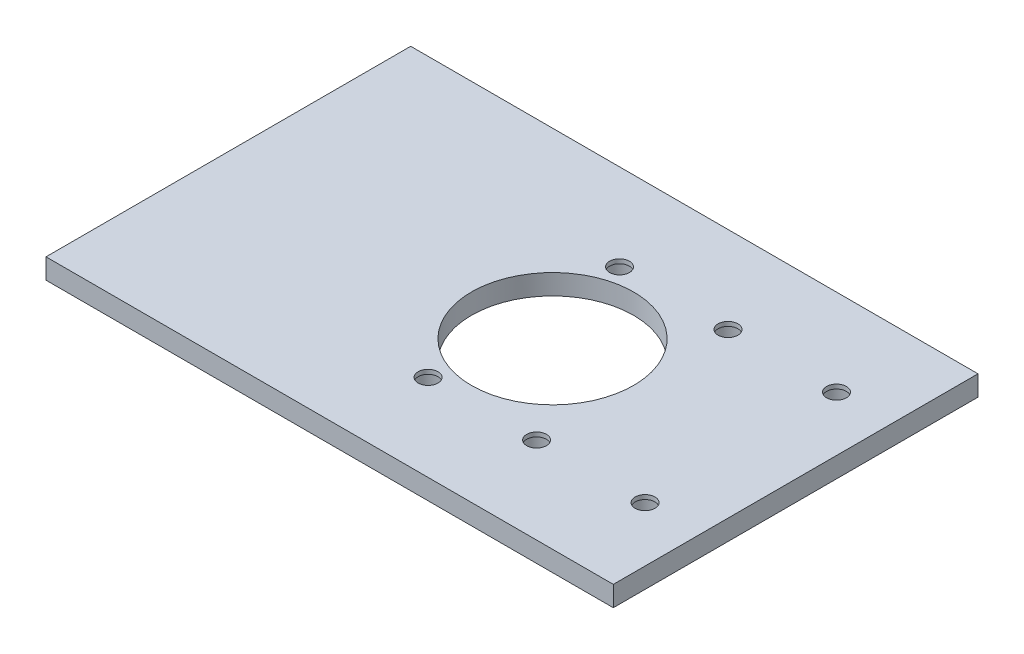
SolidWorks part; units mm, degrees
material "6061-T6 (SS)"
ref_plane "Front Plane" through (0, 0, 0) normal (0, 0, 1) x (1, 0, 0)
ref_plane "Top Plane" through (0, 0, 0) normal (0, 1, 0) x (1, 0, 0)
ref_plane "Right Plane" through (0, 0, 0) normal (1, 0, 0) x (0, 0, -1)
sketch "Sketch1" plane through (0, 0, 0) normal (0, 1, 0) x (1, 0, 0)
  line L1 (38.1, 28.575) -> (-50.8, 28.575)
  line L2 (38.1, 28.575) -> (38.1, -28.575)
  line L3 (38.1, -28.575) -> (-50.8, -28.575)
  line L4 (-50.8, 28.575) -> (-50.8, -28.575)
  point P0 (0, 0)
  dimension "D1" = 50.8
  dimension "D2" = 28.575
  dimension "D3" = 28.575
  dimension "D4" = 38.1
extrude "Boss-Extrude1" add sketch "Sketch1" along normal mid plane 3.175
sketch "Sketch2" plane through (0, 1.5875, 0) normal (0, 1, 0) x (1, 0, 0)
  line L0 (-31.75, 19.05) -> (-44.45, 19.05)
  line L8 (-31.75, 19.05) -> (-31.75, -19.05)
  line L9 (-31.75, -19.05) -> (-44.45, -19.05)
  line L10 (-44.45, 19.05) -> (-44.45, -19.05)
  line L11 (-31.75, 19.05) -> (-44.45, -19.05) construction
  line L12 (-31.75, -19.05) -> (-44.45, 19.05) construction
  circle A0 centre (0, 0) radius 12.7
  point P8 (-38.1, 0)
  dimension "D1" = 25.4
  dimension "D2" = 12.7
  dimension "D3" = 38.1
  dimension "D4" = 38.1
  dimension "D5" = 38.1
extrude "Cut-Extrude1" cut sketch "Sketch2" against normal up to surface (3.175 mm away) contours A0 up to face at (-6.35, -1.5875, 0)
sketch "Sketch6" plane through (0, 1.5875, 0) normal (0, 1, 0) x (1, 0, 0)
  line L0 (30, -12.2) -> (-9, -12.2)
  line L1 (-12, -12.7) -> (-12, -9.2)
  line L2 (-12, -12.7) -> (-6, -17.8)
  line L3 (-6, -17.8) -> (32.6, -17.8)
  line L4 (32.6, -17.8) -> (38.6, -12.7)
  line L5 (38.6, -12.7) -> (38.6, 12.7)
  line L6 (38.6, 12.7) -> (32.6, 17.8)
  line L7 (32.6, 17.8) -> (-6, 17.8)
  line L8 (-12, 12.7) -> (-6, 17.8)
  line L9 (-12, 9.2) -> (-12, 12.7)
  line L10 (-9, 12.2) -> (30, 12.2)
  line L11 (33, 9.2) -> (33, -9.2)
  line L12 (30, 11.2) -> (-9, 11.2)
  line L13 (-11, 9.2) -> (-11, -9.2)
  line L14 (-9, -11.2) -> (30, -11.2)
  line L15 (32, -9.2) -> (32, 9.2)
  circle A0 centre (29.5, 15) radius 1.35
  circle A1 centre (29.5, -15) radius 1.35
  circle A2 centre (35.8, 8.5) radius 1.35
  circle A3 centre (12.5, 15) radius 1.35
  circle A4 centre (-4.5, 15) radius 1.35
  circle A5 centre (35.8, -8.5) radius 1.35
  circle A6 centre (12.5, -15) radius 1.35
  circle A7 centre (-4.5, -15) radius 1.35
  arc A8 (-12, -9.2) -> (-9, -12.2) centre (-9, -9.2) ccw
  arc A9 (-9, 12.2) -> (-12, 9.2) centre (-9, 9.2) ccw
  arc A10 (33, 9.2) -> (30, 12.2) centre (30, 9.2) ccw
  arc A11 (30, -12.2) -> (33, -9.2) centre (30, -9.2) ccw
  circle A12 centre (0, 0) radius 2.85
  spline S0 degree 3 poles (32, 9.2) (31.9994, 10.252) (31.055, 11.1994) (30, 11.2) knots 0 0 0 0 1 1 1 1
  spline S1 degree 3 poles (-9, 11.2) (-10.052, 11.1994) (-10.9994, 10.255) (-11, 9.2) knots 0 0 0 0 1 1 1 1
  spline S2 degree 3 poles (-11, -9.2) (-10.9994, -10.252) (-10.055, -11.1994) (-9, -11.2) knots 0 0 0 0 1 1 1 1
  spline S3 degree 3 poles (30, -11.2) (31.052, -11.1994) (31.9994, -10.255) (32, -9.2) knots 0 0 0 0 1 1 1 1
hole_wizard "CBORE for M2.5 SHCS1" positions "Sketch9" profile "Sketch10" counterbore size "M2.5" standard "ANSI Metric"
sketch "Sketch9" plane through (0, -1.5875, 0) normal (0, -1, 0) x (-1, 0, 0)
  point P0 (-29.5, 15)
  point P3 (-12.5, 15)
  point P6 (4.5, 15)
  point P9 (-29.5, -15)
  point P12 (-12.5, -15)
  point P15 (4.5, -15)
sketch "Sketch10" plane through (29.5, -1.5875, -15) normal (1, 0, 0) x (0, 0, -1)
  line L0 (0, 0) -> (0, 153.3313)
  line L1 (0, 153.3313) -> (1.55, 152.4)
  line L2 (1.55, 152.4) -> (1.55, 2.5)
  line L3 (1.55, 2.5) -> (2.75, 2.5)
  line L5 (2.75, 2.5) -> (2.75, 0.025)
  line L6 (2.75, 0.025) -> (2.775, 0)
  line L7 (2.775, 0) -> (0, 0)
  line L8 (-2.75, 0.025) -> (-2.775, 0) construction
  line L10 (0, 153.3313) -> (-1.55, 152.4) construction
  line L11 (0, -6.35) -> (0, 107.95) construction
  dimension "Hole Dia." = 3.1
  dimension "Hole Depth" = 152.4
  dimension "C'Bore Dia." = 5.5
  dimension "C'Bore Depth" = 2.5
  dimension "Near C'Sink Dia." = 5.55
  dimension "Near C'Sink Angle" = 90
  dimension "Drill Angle" = 118
